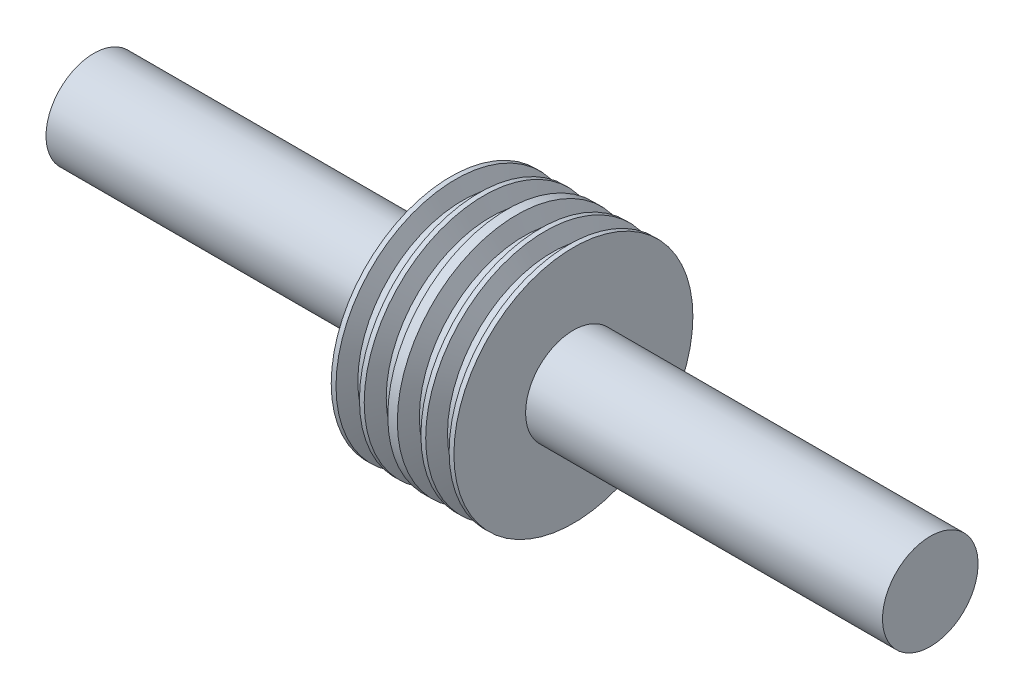
SolidWorks part; units mm, degrees
ref_plane "Front Plane" through (0, 0, 0) normal (0, 0, 1) x (1, 0, 0)
ref_plane "Top Plane" through (0, 0, 0) normal (0, 1, 0) x (1, 0, 0)
ref_plane "Right Plane" through (0, 0, 0) normal (1, 0, 0) x (0, 0, -1)
sketch "Sketch1" plane through (0, 0, 0) normal (0, 0, 1) x (1, 0, 0)
  line L0 (0, 0) -> (70, 0) construction
  line L1 (35, 0) -> (35, 10) construction
  line L2 (29.8669, 10) -> (29.8669, 4)
  line L7 (29.8669, 4) -> (0, 4)
  line L8 (0, 4) -> (0, 0)
  line L10 (0, 0) -> (70, 0)
  line L11 (70, 0) -> (70, 4)
  line L12 (70, 4) -> (40.1331, 4)
  line L13 (35, 10) -> (32.2282, 10) construction
  line L14 (35.4, 10) -> (34.6, 10)
  line L15 (34.6, 10) -> (34.0141, 8.7435)
  line L16 (34.0141, 8.7435) -> (33.2141, 8.7435)
  line L17 (33.2141, 8.7435) -> (32.6282, 10)
  line L18 (32.6282, 10) -> (32.2282, 10)
  line L19 (32.2282, 10) -> (31.6476, 8.7548)
  line L20 (31.6476, 8.7548) -> (30.8476, 8.7548)
  line L21 (30.8476, 8.7548) -> (30.2669, 10)
  line L22 (30.2669, 10) -> (29.8669, 10)
  line L27 (40.1331, 4) -> (40.1331, 10)
  line L29 (39.7331, 10) -> (40.1331, 10)
  line L30 (39.1524, 8.7548) -> (39.7331, 10)
  line L31 (38.3524, 8.7548) -> (39.1524, 8.7548)
  line L32 (37.7718, 10) -> (38.3524, 8.7548)
  line L33 (37.3718, 10) -> (37.7718, 10)
  line L34 (36.7859, 8.7435) -> (37.3718, 10)
  line L35 (35.9859, 8.7435) -> (36.7859, 8.7435)
  line L36 (35.4, 10) -> (35.9859, 8.7435)
  line L37 (30.2669, 10) -> (29.8669, 10) construction
  dimension "D1" = 70
  dimension "D2" = 10
  dimension "D4" = 4
revolve "Revolve1" add sketch "Sketch1" angle 360 about L10
